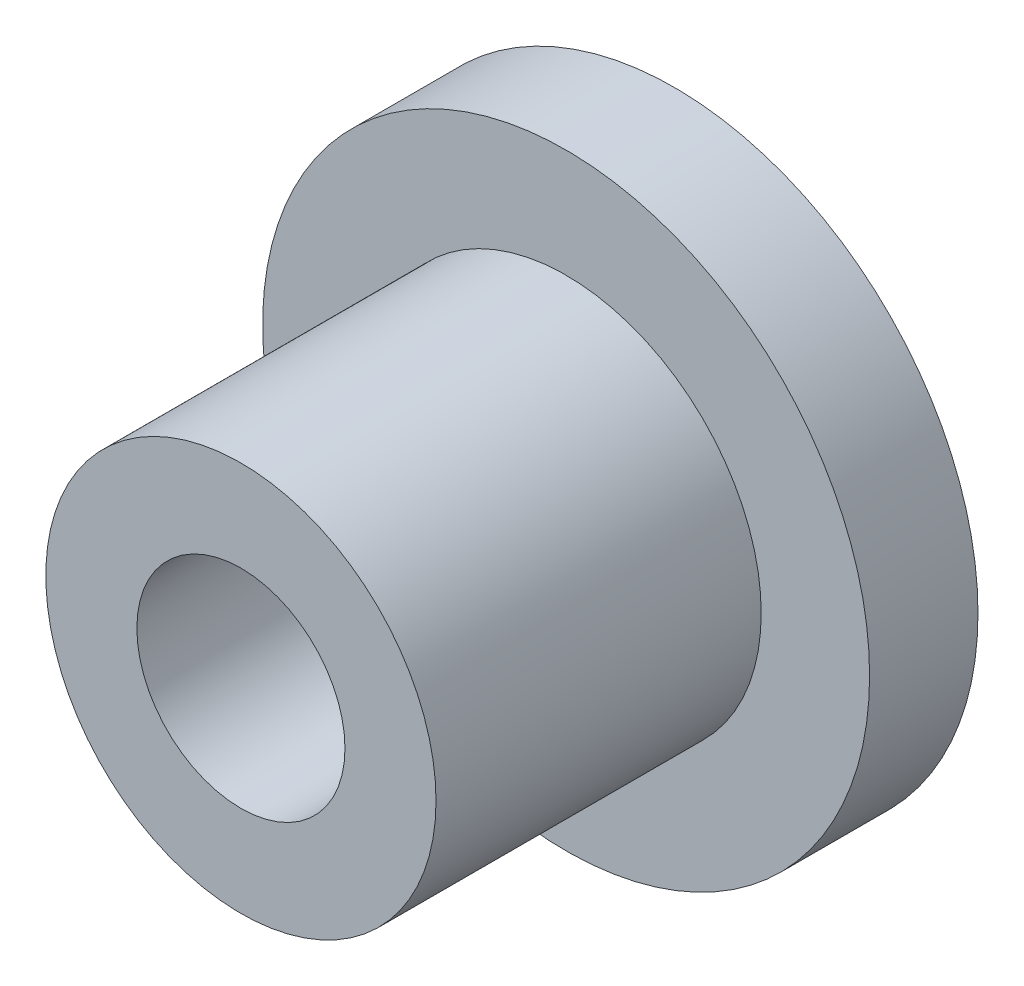
SolidWorks part; units mm, degrees
ref_plane "前视基准面" through (0, 0, 0) normal (0, 0, 1) x (1, 0, 0)
ref_plane "上视基准面" through (0, 0, 0) normal (0, 1, 0) x (1, 0, 0)
ref_plane "右视基准面" through (0, 0, 0) normal (1, 0, 0) x (0, 0, -1)
other "Configuration Table"
sketch "Sketch1" plane through (0, 0, 0) normal (0, 0, 1) x (1, 0, 0)
  circle A0 centre (0, 0) radius 7
  dimension "D1" = 14
extrude "Boss-Extrude1" add sketch "Sketch1" along normal blind 2.5
sketch "Sketch2" plane through (0, 0, 2.5) normal (0, 0, 1) x (1, 0, 0)
  circle A0 centre (0, 0) radius 4.5
  dimension "D1" = 9
extrude "Boss-Extrude2" add sketch "Sketch2" along normal blind 7.5
sketch "Sketch3" plane through (0, 0, 10) normal (0, 0, 1) x (1, 0, 0)
  circle A1 centre (0, 0) radius 2.4
  dimension "D1" = 4.8
extrude "Cut-Extrude1" cut sketch "Sketch3" against normal blind 5
